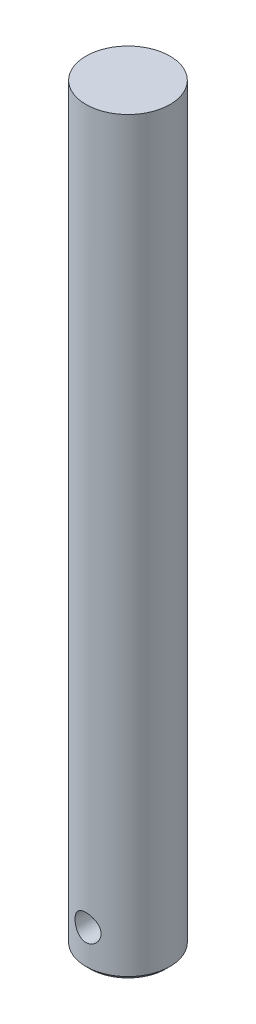
SolidWorks part; units mm, degrees
material "1060-H18"
ref_plane "前视基准面" through (0, 0, 0) normal (0, 0, 1) x (1, 0, 0)
ref_plane "上视基准面" through (0, 0, 0) normal (0, 1, 0) x (1, 0, 0)
ref_plane "右视基准面" through (0, 0, 0) normal (1, 0, 0) x (0, 0, -1)
other "Configuration Table"
sketch "Sketch1" plane through (0, 0, 0) normal (0, 1, 0) x (1, 0, 0)
  circle A0 centre (0, 0) radius 10
extrude "Boss-Extrude1" add sketch "Sketch1" along normal blind 178.8
chamfer "Chamfer1" distance 1 angle 45 1 edges at (0, 0, 10)
ref_plane "Plane1" through (0, 0, -10) normal (0, 0, -1) x (-1, 0, 0)
sketch "Sketch2" plane through (0, 0, -10) normal (0, 0, -1) x (-1, 0, 0)
  line L0 (0, 0) -> (0, 5.95)
  line L1 (0, 5.95) -> (0, 9.05)
  circle A0 centre (0, 9.05) radius 3.1
extrude "Cut-Extrude1" cut sketch "Sketch2" against normal blind 155
ref_plane "Plane2" through (0, 0, -10) normal (0, 0, -1) x (-1, 0, 0)
sketch "Sketch3" plane through (0, 0, -10) normal (0, 0, -1) x (-1, 0, 0)
  circle A0 centre (0, 9.05) radius 3.1
sketch "Sketch4" plane through (0, 0, 0) normal (0, 1, 0) x (1, 0, 0)
  point P0 (0, 0)
sketch "草图1" plane through (0, 0, 0) normal (0, -1, 0) x (1, 0, 0)
  circle A0 centre (0, 0) radius 2.5
extrude "切除-拉伸1" cut sketch "草图1" against normal blind 10
